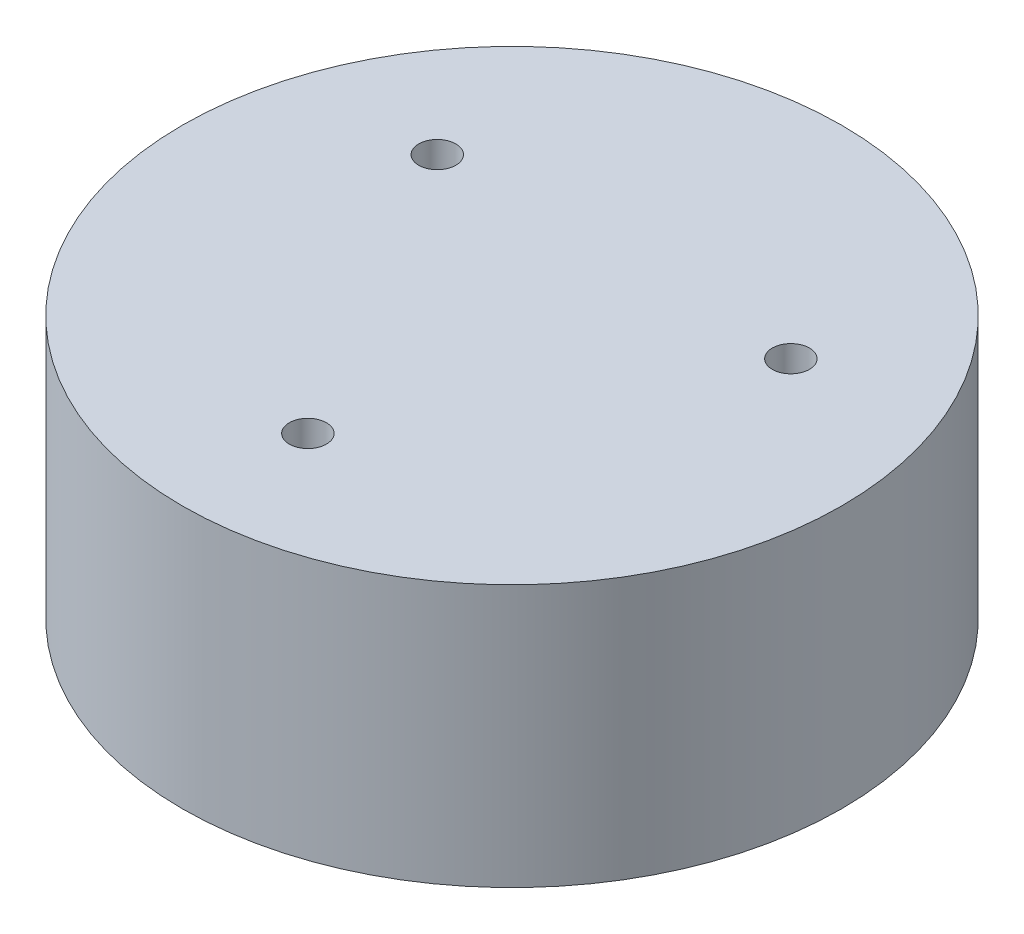
SolidWorks part; units mm, degrees
ref_plane "Front Plane" through (0, 0, 0) normal (0, 0, 1) x (1, 0, 0)
ref_plane "Top Plane" through (0, 0, 0) normal (0, 1, 0) x (1, 0, 0)
ref_plane "Right Plane" through (0, 0, 0) normal (1, 0, 0) x (0, 0, -1)
sketch "Sketch1" plane through (0, 0, 0) normal (0, 1, 0) x (1, 0, 0)
  circle A0 centre (0, 0) radius 26.65
extrude "Boss-Extrude1" add sketch "Sketch1" along normal blind 21.2
sketch "Sketch6" plane through (0, 0, 0) normal (0, -1, 0) x (-1, 0, 0)
  circle A0 centre (6.3138, -15.2429) radius 1.5
  circle A1 centre (-16.3576, 2.1535) radius 1.5
  circle A2 centre (10.0438, 13.0894) radius 1.5
  point P15 (0, 0)
  point P20 (0, 0)
  point P53 (0, 0)
  dimension "D1" = 3
extrude "Cut-Extrude2" cut sketch "Sketch6" against normal blind 8.255
sketch "Sketch7" plane through (0, 21.2, 0) normal (0, 1, 0) x (1, 0, 0)
  circle A1 centre (0, -16.5) radius 1.5
  circle A2 centre (-14.2894, 8.25) radius 1.5
  circle A3 centre (14.2894, 8.25) radius 1.5
  point P11 (0, 0)
  dimension "D1" = 3
extrude "Cut-Extrude3" cut sketch "Sketch7" against normal blind 10
